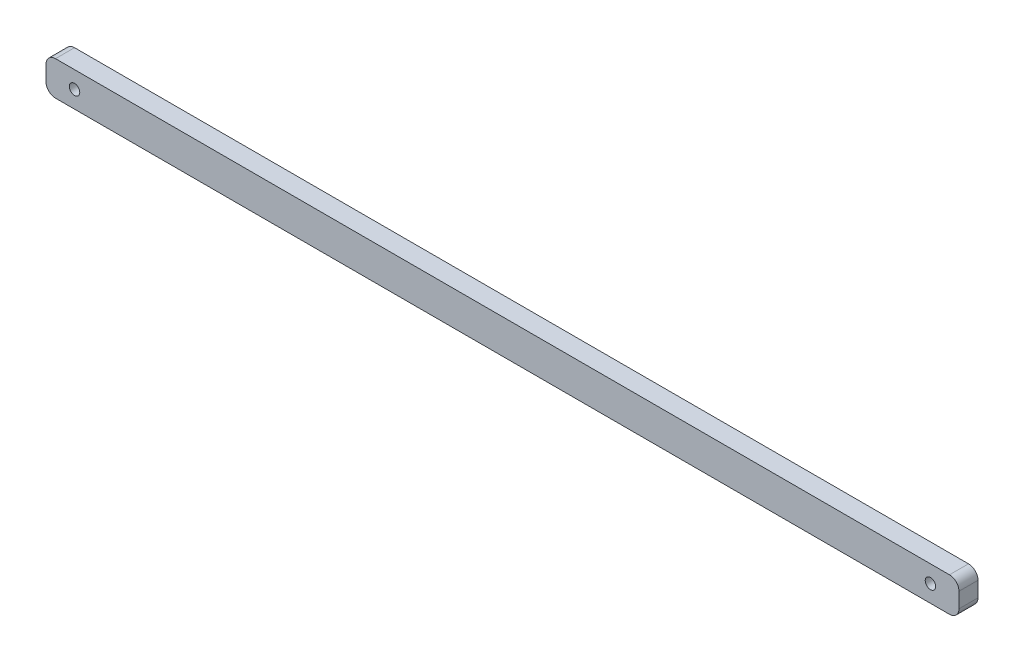
SolidWorks part; units mm, degrees
material "ABS"
ref_plane "Front" through (0, 0, 0) normal (0, 0, 1) x (1, 0, 0)
ref_plane "Top" through (0, 0, 0) normal (0, 1, 0) x (1, 0, 0)
ref_plane "Right" through (0, 0, 0) normal (1, 0, 0) x (0, 0, -1)
sketch "草图1" plane through (0, 0, 0) normal (0, 0, 1) x (1, 0, 0)
  line L0 (0, -9) -> (15, -9) construction
  line L1 (0, 0) -> (480, 0)
  line L2 (0, 0) -> (0, -18)
  line L3 (0, -18) -> (480, -18)
  line L4 (480, 0) -> (480, -18)
  line L5 (15, -9) -> (85, -9) construction
  line L6 (240, 0) -> (240, -18) construction
  circle A0 centre (15, -9) radius 2.75
  circle A1 centre (85, -9) radius 2.75 construction
  circle A2 centre (395, -9) radius 2.75 construction
  circle A3 centre (465, -9) radius 2.75
  dimension "D3" = 5.5
  dimension "D4" = 5.5
  dimension "D1" = 480
  dimension "D2" = 18
  dimension "D5" = 15
  dimension "D6" = 70
extrude "凸台-拉伸1" add sketch "草图1" along normal blind 10
fillet "圆角1" radius 5 4 edges at (480, 0, 5) (480, -18, 5) (0, 0, 5) (0, -18, 5)
